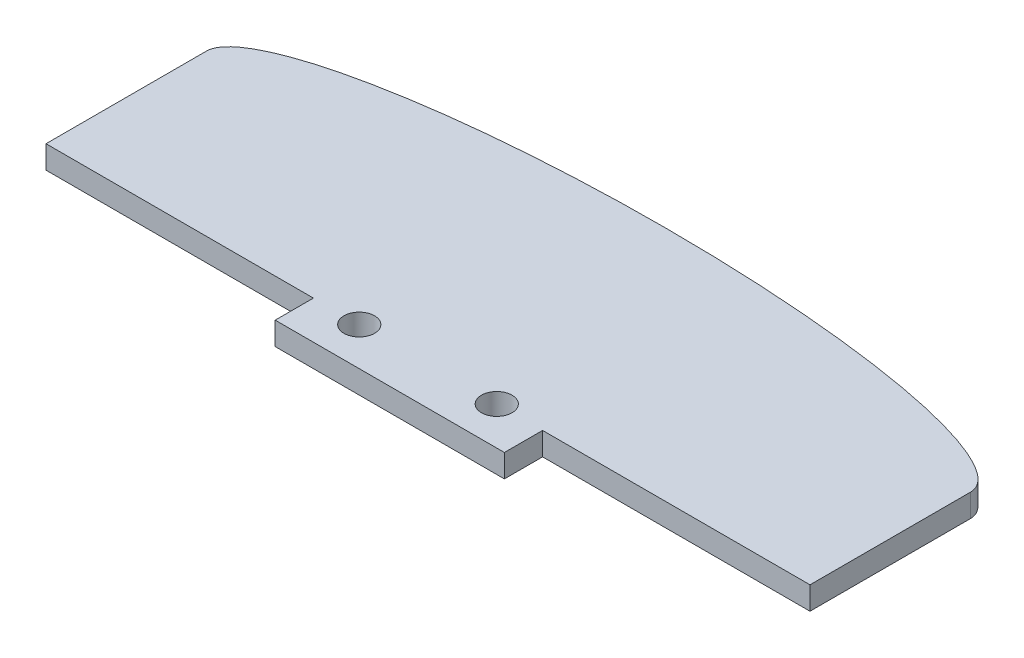
SolidWorks part; units mm, degrees
ref_plane "Front Plane" through (0, 0, 0) normal (0, 0, 1) x (1, 0, 0)
ref_plane "Top Plane" through (0, 0, 0) normal (0, 1, 0) x (1, 0, 0)
ref_plane "Right Plane" through (0, 0, 0) normal (1, 0, 0) x (0, 0, -1)
sketch "Sketch1" plane through (0, 0, 0) normal (0, 1, 0) x (1, 0, 0)
  line L0 (0, 0) -> (0, 10.5) construction
  line L2 (50, 10.5) -> (50, -10.5)
  line L3 (50, -10.5) -> (15, -10.5)
  line L4 (-50, 10.5) -> (-50, -10.5)
  line L5 (50, 10.5) -> (-50, -10.5) construction
  line L6 (50, -10.5) -> (-50, 10.5) construction
  line L7 (-15, -10.5) -> (-15, -15.5)
  line L8 (-15, -15.5) -> (15, -15.5)
  line L9 (15, -15.5) -> (15, -10.5)
  line L10 (-15, -10.5) -> (-50, -10.5)
  circle A0 centre (-9, -10.5) radius 2
  circle A1 centre (9, -10.5) radius 2
  ellipse E0 centre (0, 10.5) end of major axis (-50, 10.5) minor radius 10 (50, 10.5) -> (-50, 10.5) ccw
  point P0 (0, 0)
  dimension "D6" = 6
  dimension "D1" = 100
  dimension "D2" = 21
  dimension "D3" = 35
  dimension "D4" = 30
  dimension "D5" = 5
  dimension "D7" = 6
  dimension "D8" = 5
  dimension "D9" = 5
  dimension "D10" = 0
  dimension "D11" = 36
  dimension "D12" = 21
extrude "Boss-Extrude1" add sketch "Sketch1" along normal blind 3
